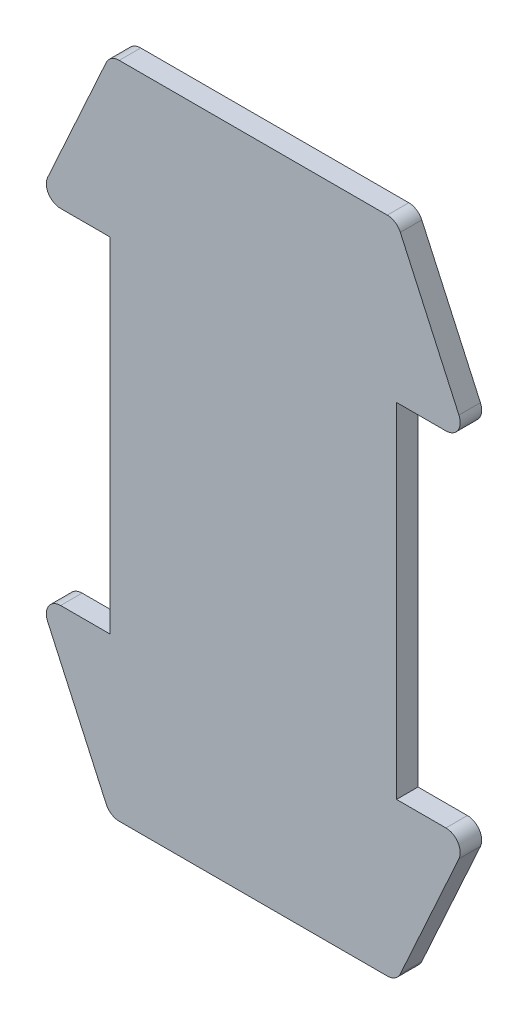
SolidWorks part; units mm, degrees
ref_plane "Front Plane" through (0, 0, 0) normal (0, 0, 1) x (1, 0, 0)
ref_plane "Top Plane" through (0, 0, 0) normal (0, 1, 0) x (1, 0, 0)
ref_plane "Right Plane" through (0, 0, 0) normal (1, 0, 0) x (0, 0, -1)
sketch "Sketch1" plane through (0, 0, 0) normal (0, 0, 1) x (1, 0, 0)
  line L0 (0, 125.4736) -> (0, -164.8543) construction
  line L1 (-208.119, 0) -> (207.473, 0) construction
  line L2 (50, 115) -> (-50, 115)
  line L3 (-50, 115) -> (-75, 60)
  line L4 (-75, 60) -> (-50, 60)
  line L5 (-50, 60) -> (-50, -60)
  line L6 (-75, -60) -> (-50, -60)
  line L7 (-50, -115) -> (-75, -60)
  line L8 (50, -115) -> (-50, -115)
  line L9 (50, -115) -> (75, -60)
  line L10 (75, -60) -> (50, -60)
  line L11 (50, 60) -> (50, -60)
  line L12 (75, 60) -> (50, 60)
  line L13 (50, 115) -> (75, 60)
  point P5 (50, 0)
  point P11 (-50, 0)
  point P15 (0, -115)
  point P20 (0, 115)
  dimension "D1" = 115
  dimension "D2" = 60
  dimension "D3" = 50
  dimension "D4" = 25
  dimension "D5" = 75
extrude "Boss-Extrude1" add sketch "Sketch1" against normal blind 7.5
fillet "Fillet1" radius 5 8 edges at (-50, -115, -3.75) (50, -115, -3.75) (75, 60, -3.75) (-75, 60, -3.75) (-75, -60, -3.75) (75, -60, -3.75) (50, 115, -3.75) (-50, 115, -3.75)
